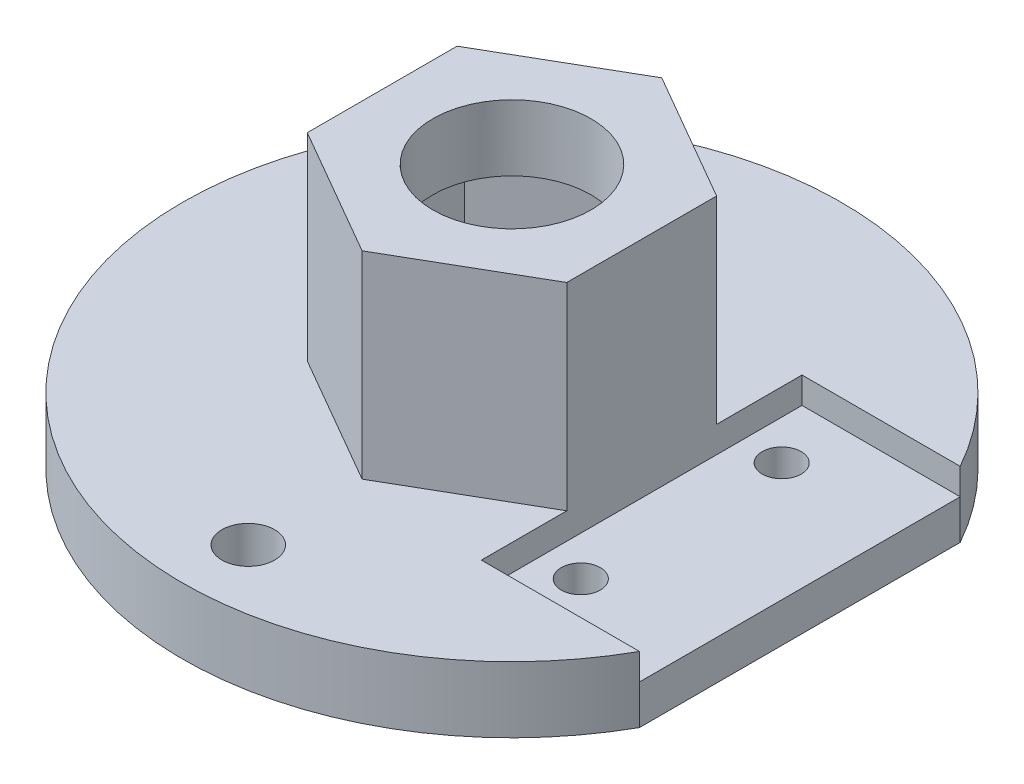
SolidWorks part; units mm, degrees
ref_plane "前视基准面" through (0, 0, 0) normal (0, 0, 1) x (1, 0, 0)
ref_plane "上视基准面" through (0, 0, 0) normal (0, 1, 0) x (1, 0, 0)
ref_plane "右视基准面" through (0, 0, 0) normal (1, 0, 0) x (0, 0, -1)
other "Configuration Table"
sketch "草图1" plane through (0, 0, 0) normal (0, 1, 0) x (1, 0, 0)
  line L0 (0, 0) -> (0, -20)
  line L1 (0, 0) -> (17.3205, 10)
  line L2 (0, 0) -> (-17.3205, 10)
  circle A0 centre (-17.3205, 10) radius 2
  circle A1 centre (17.3205, 10) radius 2
  circle A2 centre (0, -20) radius 2
  circle A3 centre (0, 0) radius 25
  circle A4 centre (0, 0) radius 15
extrude "凸台-拉伸1" add sketch "草图1" along normal blind 5
sketch "草图2" plane through (0, 5, 0) normal (0, 1, 0) x (1, 0, 0)
  line L0 (0, 0) -> (-22.5, 0)
  line L6 (-31.39, 10.16) -> (-22.8424, 10.16)
  line L7 (-31.39, -10.16) -> (-22.8424, -10.16)
  line L8 (-22.8424, -10.16) -> (-22.8424, 10.16)
  line L10 (-31.39, 10.16) -> (-31.39, -10.16)
  circle A0 centre (-25.04, 7.62) radius 1.48
  circle A1 centre (-25.04, -7.62) radius 1.48
  circle A2 centre (0, 0) radius 25 construction
  circle M20 centre (0, 0) radius 25
extrude "凸台-拉伸2" add sketch "草图2" against normal blind 5 contours A1 A0 L6 L10 L7 M20 | A1 L8 A0 M20
sketch "草图3" plane through (0, 5, 0) normal (0, 1, 0) x (1, 0, 0)
  circle A0 centre (-25.04, 7.62) radius 1.48
  circle A1 centre (-25.04, -7.62) radius 1.48
extrude "切除-拉伸1" cut sketch "草图3" against normal blind 5
sketch "草图4" plane through (0, 5, 0) normal (0, 1, 0) x (1, 0, 0)
  line L1 (-31.39, 10.16) -> (-22.8424, 10.16)
  line L2 (-31.39, 10.16) -> (-31.39, -10.16)
  line L3 (-31.39, -10.16) -> (-22.8424, -10.16)
  line L4 (-22.8424, 10.16) -> (-22.8424, -10.16)
  circle A0 centre (-25.04, 7.62) radius 1.48
  circle A1 centre (-25.04, -7.62) radius 1.5326
extrude "凸台-拉伸3" add sketch "草图4" along normal blind 25 contours L2 L1 L4 L3 | A0 | A1
sketch "草图5" plane through (0, 0, 0) normal (0, -1, 0) x (1, 0, 0)
  circle A0 centre (-25.04, 7.62) radius 1.48
  circle A1 centre (-25.04, -7.62) radius 1.48
extrude "凸台-拉伸4" add sketch "草图5" against normal blind 15
sketch "草图6" plane through (0, 30, 0) normal (0, 1, 0) x (1, 0, 0)
  line L1 (-31.39, 10.16) -> (-22.8424, 10.16)
  line L2 (-31.39, 10.16) -> (-31.39, -10.16)
  line L3 (-31.39, -10.16) -> (-22.8424, -10.16)
  line L4 (-22.8424, 10.16) -> (-22.8424, -10.16)
extrude "切除-拉伸2" cut sketch "草图6" against normal blind 10
sketch "草图7" plane through (0, 20, 0) normal (0, 1, 0) x (1, 0, 0)
  circle A0 centre (-25.04, 7.62) radius 1.48
  circle A1 centre (-25.04, -7.62) radius 1.5326
extrude "切除-拉伸3" cut sketch "草图7" against normal blind 15
sketch "草图8" plane through (0, 5, 0) normal (0, 1, 0) x (1, 0, 0)
  line L6 (22.8424, 10.16) -> (22.8424, -10.16)
  line L8 (22.8424, 10.16) -> (31.39, 10.16)
  line L9 (22.8424, 10.16) -> (22.8424, -10.16)
  line L10 (22.8424, -10.16) -> (31.39, -10.16)
  line L11 (31.39, 10.16) -> (31.39, -10.16)
  line L12 (-22.8424, 10.16) -> (-31.39, 10.16)
  arc A0 (-22.8424, -10.16) -> (-22.8424, 10.16) centre (0, 0) ccw construction
  circle A1 centre (25.04, 7.62) radius 1.48
  circle A2 centre (25.04, -7.62) radius 1.48
  arc M21 (-22.8424, -10.16) -> (-22.8424, 10.16) centre (0, 0) ccw
extrude "凸台-拉伸5" add sketch "草图8" along normal up to surface (15 mm away) contours A2 L10 L11 L8 A1 M21 | A2 A1 L6 M21 up to face at (-25.04, 20, 9.1526)
sketch "草图9" plane through (0, 20, 0) normal (0, 1, 0) x (1, 0, 0)
  line L1 (-31.39, 10.16) -> (-22.8424, 10.16)
  line L2 (-31.39, 10.16) -> (-31.39, -10.16)
  line L3 (-31.39, -10.16) -> (-22.8424, -10.16)
  line L4 (-22.8424, 10.16) -> (-22.8424, -10.16)
extrude "切除-拉伸4" cut sketch "草图9" against normal up to surface (20 mm away) up to face at (0, 0, 22)
sketch "草图10" plane through (0, 0, 0) normal (0, -1, 0) x (1, 0, 0)
  line L1 (31.39, 10.16) -> (22.8424, 10.16)
  line L2 (31.39, 10.16) -> (31.39, -10.16)
  line L3 (31.39, -10.16) -> (22.8424, -10.16)
  line L4 (22.8424, 10.16) -> (22.8424, -10.16)
extrude "凸台-拉伸6" add sketch "草图10" against normal blind 10
sketch "草图11" plane through (0, 5, 0) normal (0, 1, 0) x (1, 0, 0)
  line L0 (-22.8424, -10.16) -> (-22.8424, 10.16)
  arc A0 (-22.8424, 10.16) -> (-22.8424, -10.16) centre (0, 0) ccw
  arc A1 (-22.8424, -10.16) -> (22.8424, -10.16) centre (0, 0) ccw construction
extrude "凸台-拉伸7" add sketch "草图11" against normal blind 5
sketch "草图12" plane through (0, 0, 0) normal (0, -1, 0) x (1, 0, 0)
  line L0 (0, 0) -> (31.39, 0)
  line L1 (31.39, -10.16) -> (31.39, 10.16) construction
  line L2 (31.39, 10.16) -> (22.8424, 10.16) construction
  line L3 (22.8424, -10.16) -> (31.39, -10.16) construction
  line L4 (29.7003, -10.16) -> (31.39, -10.16)
  line L5 (31.39, -10.16) -> (31.39, 0)
  line L6 (29.7003, 10.16) -> (31.39, 10.16)
  line L7 (31.39, 10.16) -> (31.39, 0)
  arc A0 (31.39, 0) -> (29.7003, 10.16) centre (0, 0) ccw
  arc A1 (31.39, 0) -> (29.7003, -10.16) centre (0, 0) cw
  line M6 (22.8424, -10.16) -> (31.39, -10.16)
  line M7 (31.39, -10.16) -> (31.39, 10.16)
  line M8 (31.39, 10.16) -> (22.8424, 10.16)
extrude "切除-拉伸5" cut sketch "草图12" against normal blind 30 contours A0 M7 M8 | A1 M7 M6
sketch "草图13" plane through (0, 0, 0) normal (0, -1, 0) x (1, 0, 0)
  circle A0 centre (0, 0) radius 15
  circle A1 centre (0, 0) radius 6.5
extrude "凸台-拉伸8" add sketch "草图13" against normal blind 5
sketch "草图14" plane through (0, 5, 0) normal (0, 1, 0) x (1, 0, 0)
  circle A0 centre (25.04, 7.62) radius 1.48
  circle A1 centre (25.04, -7.62) radius 1.48
extrude "切除-拉伸6" cut sketch "草图14" against normal blind 5
sketch "草图15" plane through (0, 20, 0) normal (0, 1, 0) x (1, 0, 0)
  line L1 (22.8424, 10.16) -> (37.6146, 10.16)
  line L2 (22.8424, 10.16) -> (22.8424, -12.0953)
  line L3 (22.8424, -12.0953) -> (37.6146, -12.0953)
  line L4 (37.6146, 10.16) -> (37.6146, -12.0953)
extrude "切除-拉伸7" cut sketch "草图15" against normal up to surface (15 mm away) up to face at (17.3205, 5, -8)
sketch "草图16" plane through (0, 5, 0) normal (0, 1, 0) x (1, 0, 0)
  circle A0 centre (0, 0) radius 6.5
  circle A1 centre (0, 0) radius 6
extrude "凸台-拉伸9" add sketch "草图16" against normal blind 5
sketch "草图17" plane through (0, 5, 0) normal (0, 1, 0) x (1, 0, 0)
  line L1 (29.7003, -10.16) -> (22.8424, -10.16)
  line L2 (29.7003, -10.16) -> (29.7003, 10.16)
  line L3 (29.7003, 10.16) -> (22.8424, 10.16)
  line L4 (22.8424, -10.16) -> (22.8424, 10.16)
  line L5 (29.7003, 10.16) -> (33.8172, 10.16)
  line L6 (29.7003, 10.16) -> (29.7003, -10.16)
  line L7 (29.7003, -10.16) -> (33.8172, -10.16)
  line L8 (33.8172, 10.16) -> (33.8172, -10.16)
  line M8 (22.8424, -10.16) -> (29.7003, -10.16)
  arc M9 (29.7003, -10.16) -> (29.7003, 10.16) centre (0, 0) ccw
  line M10 (29.7003, 10.16) -> (22.8424, 10.16)
  circle M11 centre (25.04, -7.62) radius 1.48
  circle M12 centre (25.04, 7.62) radius 1.48
extrude "切除-拉伸8" cut sketch "草图17" against normal blind 2 contours L4 L2 M8 M10 M12 M11 | L8 L5 L7 M9 | L2 M9
sketch "草图18" plane through (0, 5, 0) normal (0, 1, 0) x (1, 0, 0)
  line L0 (22.8424, 0) -> (21.8424, 0)
  line L1 (22.8424, -10.16) -> (22.8424, 10.16) construction
  line L2 (21.8424, 0) -> (21.8424, 12.1618)
  line L3 (21.8424, 0) -> (21.8424, -12.1618)
  line L4 (22.8424, 10.16) -> (22.8424, -10.16)
  arc A0 (22.8424, 10.16) -> (22.8424, -10.16) centre (0, 0) ccw construction
  arc A1 (22.8424, 10.16) -> (21.8424, 12.1618) centre (0, 0) ccw
  arc A2 (22.8424, -10.16) -> (21.8424, -12.1618) centre (0, 0) cw
  arc M6 (22.8424, 10.16) -> (22.8424, -10.16) centre (0, 0) ccw
  line M7 (22.8424, -10.16) -> (22.8424, 10.16)
extrude "切除-拉伸9" cut sketch "草图18" against normal blind 2 contours L2 L0 M7 M6 | L0 L3 M6 M7
sketch "草图19" plane through (0, 5, 0) normal (0, 1, 0) x (1, 0, 0)
  line L0 (21.8424, 12.1618) -> (9.8424, 12.1618)
  line L1 (21.8424, -12.1618) -> (9.8424, -12.1618)
  line L2 (9.8424, -12.1618) -> (9.8424, 12.1618)
  line L3 (21.8424, 12.1618) -> (21.8424, -12.1618)
extrude "切除-拉伸10" cut sketch "草图19" against normal blind 2 contours L3 L1 L2 L0
sketch "草图20" plane through (0, 3, 0) normal (0, 1, 0) x (1, 0, 0)
  circle A0 centre (17.3205, 10) radius 2
extrude "凸台-拉伸10" add sketch "草图20" against normal blind 3
sketch "草图21" plane through (0, 3, 0) normal (0, 1, 0) x (1, 0, 0)
  line L0 (22.8424, 10.16) -> (22.8424, -10.16)
  line L1 (25.04, 7.62) -> (22.8424, 7.62)
  line L2 (9.8424, -7.62) -> (12.8424, -7.62)
  line L3 (9.8424, -12.1618) -> (9.8424, 12.1618) construction
  line L4 (9.8424, 7.62) -> (12.8424, 7.62)
  line L5 (21.8424, 12.1618) -> (21.8424, -12.1618)
  line L6 (9.8424, -12.1618) -> (9.8424, 12.1618) construction
  circle A0 centre (12.8424, 7.62) radius 1.48
  circle A1 centre (12.8424, -7.62) radius 1.48
extrude "切除-拉伸11" cut sketch "草图21" against normal blind 3
sketch "草图22" plane through (0, 3, 0) normal (0, 1, 0) x (1, 0, 0)
  line L1 (21.8424, 12.1618) -> (32.3794, 12.1618)
  line L2 (21.8424, 12.1618) -> (21.8424, -12.1618)
  line L3 (21.8424, -12.1618) -> (32.3794, -12.1618)
  line L4 (32.3794, 12.1618) -> (32.3794, -12.1618)
extrude "切除-拉伸12" cut sketch "草图22" against normal blind 3
sketch "草图23" plane through (0, 5, 0) normal (0, 1, 0) x (1, 0, 0)
  circle A0 centre (0, 0) radius 9.8424
  circle A1 centre (0, 0) radius 6
extrude "凸台-拉伸11" add sketch "草图23" along normal blind 15
sketch "草图24" plane through (0, 0, 0) normal (0, -1, 0) x (1, 0, 0)
  line L4 (8.5, 4.9075) -> (0, 9.815)
  line L5 (0, 9.815) -> (-8.5, 4.9075)
  line L6 (-8.5, 4.9075) -> (-8.5, -4.9075)
  line L7 (-8.5, -4.9075) -> (0, -9.815)
  line L8 (0, -9.815) -> (8.5, -4.9075)
  line L9 (8.5, -4.9075) -> (8.5, 4.9075)
  circle A0 centre (0, 0) radius 8.5 construction
extrude "切除-拉伸13" cut sketch "草图24" against normal blind 15 contours L4 L5 L6 L7 L8 L9
sketch "草图25" plane through (0, 20, 0) normal (0, 1, 0) x (1, 0, 0)
  line L6 (9.8424, 5.6825) -> (0, 11.365)
  line L7 (0, 11.365) -> (-9.8424, 5.6825)
  line L8 (-9.8424, 5.6825) -> (-9.8424, -5.6825)
  line L9 (-9.8424, -5.6825) -> (0, -11.365)
  line L10 (0, -11.365) -> (9.8424, -5.6825)
  line L11 (9.8424, -5.6825) -> (9.8424, 5.6825)
  circle A0 centre (0, 0) radius 9.8424 construction
  circle A1 centre (0, 0) radius 6
extrude "凸台-拉伸12" add sketch "草图25" against normal blind 15
sketch "草图27" plane through (0, 0, 0) normal (0, -1, 0) x (1, 0, 0)
  line L1 (0, 9.815) -> (-8.5, 4.9075)
  line L2 (-8.5, 4.9075) -> (-8.5, -4.9075)
  line L3 (-8.5, -4.9075) -> (0, -9.815)
  line L4 (0, -9.815) -> (8.5, -4.9075)
  line L5 (8.5, -4.9075) -> (8.5, 4.9075)
  line L6 (8.5, 4.9075) -> (0, 9.815)
  circle A0 centre (0, 0) radius 8.5 construction
extrude "切除-拉伸14" cut sketch "草图27" against normal blind 15
